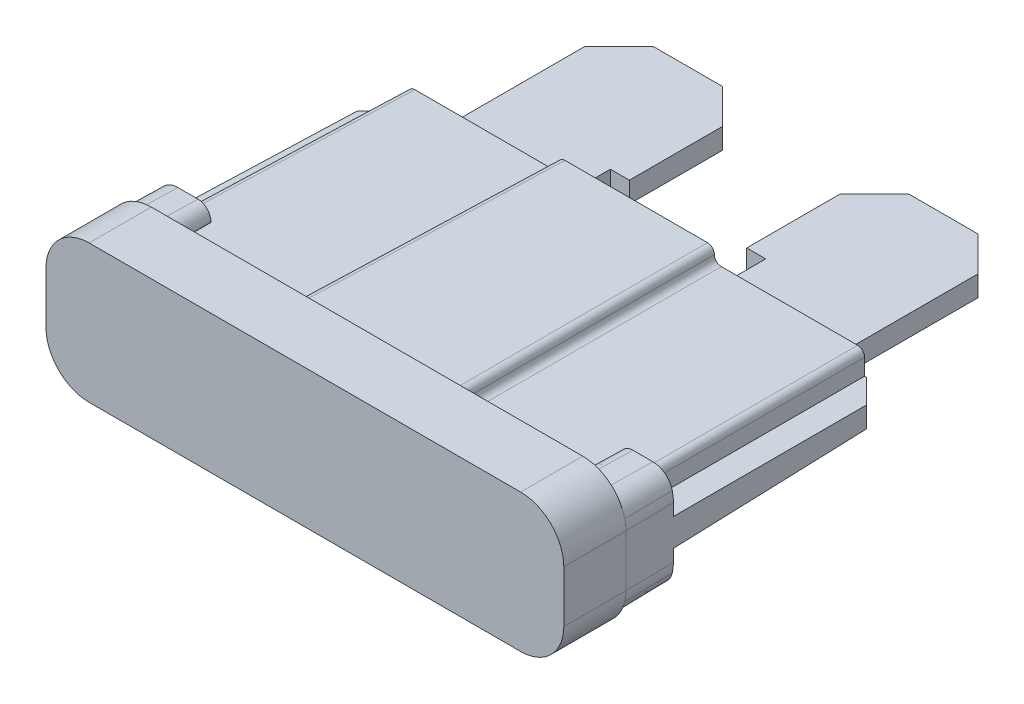
SolidWorks part; units mm, degrees
ref_plane "Plane1" through (0, 0, 0) normal (0, 0, 1) x (1, 0, 0)
ref_plane "Plane2" through (0, 0, 0) normal (0, 1, 0) x (1, 0, 0)
ref_plane "Plane3" through (0, 0, 0) normal (1, 0, 0) x (0, 0, -1)
sketch "Sketch1" plane through (0, 0, 0) normal (0, 0, 1) x (1, 0, 0)
  line L0 (0, 0) -> (0, 6.3939) construction
  line L1 (-9.525, 2.54) -> (9.525, 2.54)
  line L2 (-9.525, 2.54) -> (-9.525, -2.54)
  line L3 (-9.525, -2.54) -> (9.525, -2.54)
  line L4 (9.525, 2.54) -> (9.525, -2.54)
  line L5 (0, 0) -> (8.7866, 0) construction
  point P8 (0, 2.54)
  point P10 (9.525, 0)
  dimension "D1" = 19.05
  dimension "D2" = 5.08
extrude "Base-Extrude" add sketch "Sketch1" against normal blind 2.286
fillet "Fillet1" radius 1.5875 4 edges at (-9.525, 2.54, -1.143) (9.525, 2.54, -1.143) (9.525, -2.54, -1.143) (-9.525, -2.54, -1.143)
sketch "Sketch2" plane through (0, 0, -2.286) normal (0, 0, -1) x (-1, 0, 0)
  line L0 (0, 0) -> (10.4993, 0) construction
  line L1 (-3.048, 1.905) -> (3.048, 1.905)
  line L2 (-3.048, 1.905) -> (-3.048, 1.397)
  line L3 (-3.048, -1.905) -> (3.048, -1.905)
  line L4 (3.048, 1.905) -> (3.048, 1.397)
  line L5 (-8.5725, 1.397) -> (-3.048, 1.397)
  line L6 (-8.5725, 1.397) -> (-8.5725, -1.397)
  line L7 (-8.5725, -1.397) -> (-3.048, -1.397)
  line L8 (8.5725, 1.397) -> (8.5725, -1.397)
  line L9 (0, 0) -> (0, 4.7084) construction
  line L10 (3.048, -1.397) -> (3.048, -1.905)
  line L11 (3.048, 1.397) -> (8.5725, 1.397)
  line L12 (-3.048, -1.397) -> (-3.048, -1.905)
  line L13 (3.048, -1.397) -> (8.5725, -1.397)
  point P13 (0, 1.905)
  point P18 (8.5725, 0)
  dimension "D1" = 3.81
  dimension "D2" = 6.096
  dimension "D3" = 17.145
  dimension "D4" = 2.794
extrude "Boss-Extrude3" add sketch "Sketch2" along normal offset from surface 12.192 draft 1
fillet "Fillet4" radius 0.254 12 edges at (-2.9615, 1.8185, -7.239) (-2.9615, 1.3105, -7.239) (-8.486, 1.3105, -7.239) (-8.486, -1.3105, -7.239) (-2.9615, -1.3105, -7.239) (-2.9615, -1.8185, -7.239) (2.9615, -1.8185, -7.239) (2.9615, -1.3105, -7.239) (8.486, -1.3105, -7.239) (8.486, 1.3105, -7.239) (2.9615, 1.3105, -7.239) (2.9615, 1.8185, -7.239)
sketch "Sketch3" plane through (0, 0, -2.286) normal (0, 0, -1) x (-1, 0, 0)
  line L0 (-9.525, -0.9525) -> (-9.525, 0.9525) construction
  line L1 (-9.525, -0.9525) -> (-9.525, 0.9525)
  line L2 (-8.7407, 1.905) -> (-8.001, 1.905)
  line L3 (-7.493, 1.397) -> (-7.493, -1.397)
  line L4 (-8.7407, -1.905) -> (-8.001, -1.905)
  line L5 (0, 0) -> (-12.6347, 0) construction
  line L6 (0, 0) -> (0, 9.8799) construction
  line L7 (8.7407, -1.905) -> (8.001, -1.905)
  line L8 (7.493, 1.397) -> (7.493, -1.397)
  line L9 (8.7407, 1.905) -> (8.001, 1.905)
  line L10 (9.525, -0.9525) -> (9.525, 0.9525)
  arc A0 (-9.525, -0.9525) -> (-7.9375, -2.54) centre (-7.9375, -0.9525) ccw construction
  arc A1 (-7.9375, 2.54) -> (-9.525, 0.9525) centre (-7.9375, 0.9525) ccw construction
  arc A2 (-8.001, -1.905) -> (-7.493, -1.397) centre (-8.001, -1.397) ccw
  arc A3 (-8.001, 1.905) -> (-7.493, 1.397) centre (-8.001, 1.397) cw
  arc A6 (-9.525, -0.9525) -> (-9.4822, -1.3188) centre (-7.9375, -0.9525) ccw
  arc A7 (-9.4822, 1.3188) -> (-9.525, 0.9525) centre (-7.9375, 0.9525) ccw
  arc A8 (-9.4822, 1.3188) -> (-8.7407, 1.905) centre (-8.7407, 1.143) cw
  arc A9 (-8.7407, -1.905) -> (-9.4822, -1.3188) centre (-8.7407, -1.143) cw
  arc A10 (8.7407, -1.905) -> (9.4822, -1.3188) centre (8.7407, -1.143) ccw
  arc A11 (9.4822, 1.3188) -> (8.7407, 1.905) centre (8.7407, 1.143) ccw
  arc A12 (9.4822, 1.3188) -> (9.525, 0.9525) centre (7.9375, 0.9525) cw
  arc A13 (9.525, -0.9525) -> (9.4822, -1.3188) centre (7.9375, -0.9525) cw
  arc A14 (8.001, 1.905) -> (7.493, 1.397) centre (8.001, 1.397) ccw
  arc A15 (8.001, -1.905) -> (7.493, -1.397) centre (8.001, -1.397) cw
  point P22 (-7.493, 0)
  dimension "D1" = 0.762
  dimension "D4" = 0.508
  dimension "D2" = 3.81
  dimension "D3" = 2.032
extrude "Boss-Extrude4" add sketch "Sketch3" along normal blind 1.778 draft 1
sketch "Sketch5" plane through (0, 0, -4.064) normal (0, 0, -1) x (-1, 0, 0)
  line L0 (-9.494, 0.9525) -> (-9.494, -0.9525) construction
  line L1 (-9.494, 0.508) -> (-9.494, -0.508)
  line L2 (-9.494, 0.508) -> (-7.6322, 0.508)
  line L3 (-7.6322, 0.508) -> (-7.6322, -0.508)
  line L4 (-7.6322, -0.508) -> (-9.494, -0.508)
  line L5 (0, 0) -> (-10.205, 0) construction
  line L6 (0, 0) -> (0, 4.9575) construction
  line L7 (7.6322, -0.508) -> (9.494, -0.508)
  line L8 (7.6322, 0.508) -> (7.6322, -0.508)
  line L9 (9.494, 0.508) -> (7.6322, 0.508)
  line L10 (9.494, 0.508) -> (9.494, -0.508)
  point P9 (-9.494, 0)
  dimension "D1" = 1.016
extrude "Boss-Extrude6" add sketch "Sketch5" along normal up to surface (8.128 mm away) draft 1
sketch "Sketch6" plane through (0, 0, 0) normal (0, 1, 0) x (1, 0, 0)
  line L0 (-7.239, 12.192) -> (-7.239, 17.526)
  line L1 (-3.1291, 12.192) -> (-8.1456, 12.192) construction
  line L2 (-7.239, 17.526) -> (-5.969, 18.796)
  line L3 (-5.969, 18.796) -> (-3.429, 18.796)
  line L4 (-3.429, 18.796) -> (-2.159, 17.526)
  line L5 (-2.159, 17.526) -> (-2.159, 14.097)
  line L6 (-2.159, 14.097) -> (-2.8575, 14.097)
  line L7 (-2.8575, 14.097) -> (-2.8575, 12.192)
  line L8 (0, 0) -> (0, 22.2544) construction
  line L9 (-2.8575, 12.192) -> (-7.239, 12.192)
  line L10 (7.9375, 0) -> (-7.9375, 0) construction
  line L11 (2.6211, 12.192) -> (-2.6211, 12.192) construction
  line L12 (2.8575, 12.192) -> (7.239, 12.192)
  line L13 (2.8575, 14.097) -> (2.8575, 12.192)
  line L14 (2.159, 14.097) -> (2.8575, 14.097)
  line L15 (2.159, 17.526) -> (2.159, 14.097)
  line L16 (3.429, 18.796) -> (2.159, 17.526)
  line L17 (5.969, 18.796) -> (3.429, 18.796)
  line L18 (7.239, 17.526) -> (5.969, 18.796)
  line L19 (7.239, 12.192) -> (7.239, 17.526)
  dimension "D1" = 14.478
  dimension "D2" = 18.796
  dimension "D3" = 45
  dimension "D4" = 1.27
  dimension "D5" = 5.08
  dimension "D6" = 5.715
  dimension "D7" = 1.905
extrude "Blades" add sketch "Sketch6" along normal mid plane 0.762
chamfer "Chamfer1" distance 0.889 angle 45 2 edges at (9.3521, 0, -12.192) (-9.3521, 0, -12.192)
